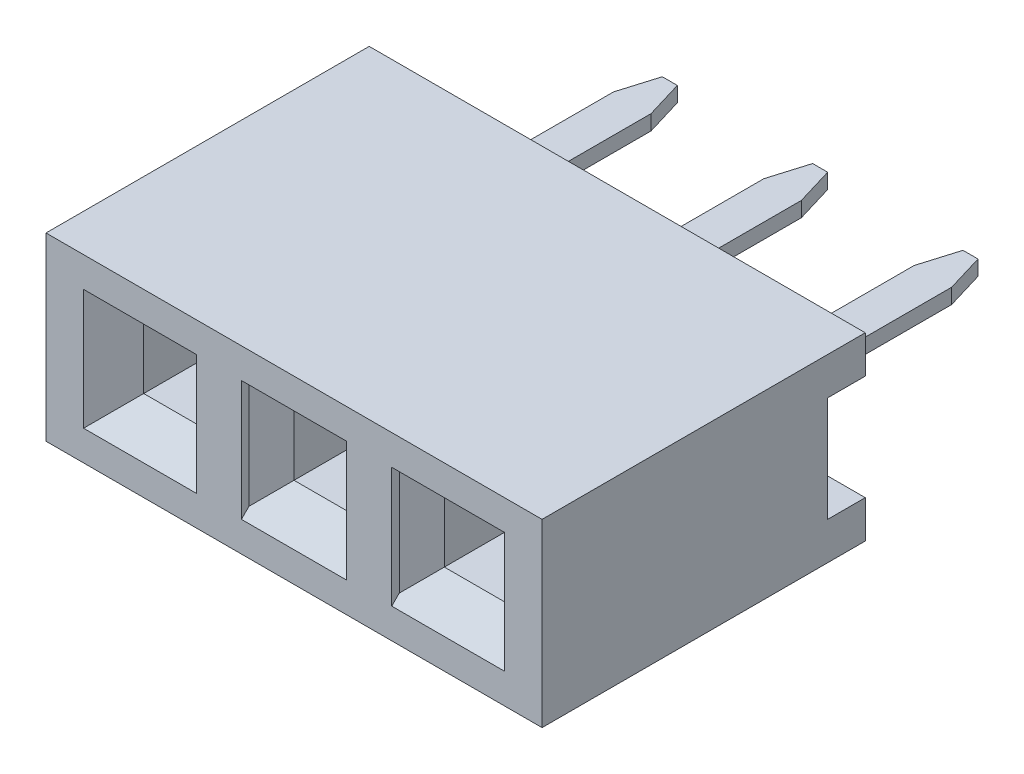
SolidWorks part; units mm, degrees
ref_plane "Front Plane" through (0, 0, 0) normal (0, 0, 1) x (1, 0, 0)
ref_plane "Top Plane" through (0, 0, 0) normal (0, 1, 0) x (1, 0, 0)
ref_plane "Right Plane" through (0, 0, 0) normal (1, 0, 0) x (0, 0, -1)
sketch "Sketch1" plane through (0, 0, 0) normal (1, 0, 0) x (0, -1, 0)
  line L0 (0, 0) -> (0, -4.3) construction
  line L1 (-1.2, 0) -> (1.2, 0)
  line L2 (-1.2, 0) -> (-1.2, -4.3)
  line L3 (-1.2, -4.3) -> (1.2, -4.3)
  line L4 (1.2, 0) -> (1.2, -4.3)
  point P0 (0, 0)
  dimension "D1" = 2.4
  dimension "D2" = 4.3
extrude "Boss-Extrude1" add sketch "Sketch1" along normal mid plane 2.6
sketch "Эскиз1" plane through (1.3, 0, 0) normal (1, 0, 0) x (0, 0, -1)
  line L0 (0, -0.7) -> (-0.5, -0.7)
  line L1 (0, -1.2) -> (0, 1.2) construction
  line L2 (-0.5, -0.7) -> (-0.5, 0.7)
  line L4 (-0.5, 0.7) -> (0, 0.7)
  line L5 (0, 0.7) -> (0, -0.7)
  line L6 (-4.3, -1.2) -> (0, -1.2) construction
  dimension "D1" = 0.5
  dimension "D2" = 0.5
  dimension "D3" = 0.5
extrude "Вырез-Вытянуть1" cut sketch "Эскиз1" against normal through all
sketch "Sketch2" plane through (0, 0, 4.3) normal (0, 0, 1) x (-1, 0, 0)
  line L0 (0, -1.2) -> (0, 1.2) construction
  line L3 (-1.3, -1.2) -> (1.3, -1.2) construction
  line L4 (-0.4, 0.4) -> (0.4, 0.4)
  line L5 (-0.4, 0.4) -> (-0.4, -0.4)
  line L6 (-0.4, -0.4) -> (0.4, -0.4)
  line L7 (0.4, 0.4) -> (0.4, -0.4)
  line L8 (-0.4, 0.4) -> (0.4, -0.4) construction
  line L9 (-0.4, -0.4) -> (0.4, 0.4) construction
  line L10 (-1.3, 1.2) -> (1.3, 1.2) construction
  point P5 (0, 0)
  dimension "D1" = 0.8
extrude "Cut-Extrude1" cut sketch "Sketch2" against normal offset from surface (3.1 mm away) 0.7 up to face at (0, 0, 0.5)
chamfer "Фаска1" distance 0.4 angle 45 4 edges at (0, -0.4, 4.3) (0.4, 0, 4.3) (0, 0.4, 4.3) (-0.4, 0, 4.3)
sketch "Sketch3" plane through (0, 0, 0) normal (0, 1, 0) x (1, 0, 0)
  line L0 (-0.25, 0) -> (-0.25, 2.2)
  line L1 (0.25, 0) -> (0.25, -0.5)
  line L2 (-0.25, 2.2) -> (-0.1, 2.7)
  line L3 (-0.1, 2.7) -> (0.1, 2.7)
  line L4 (0, 2.7) -> (0, 0) construction
  line L5 (-0.25, 0) -> (0.25, 0) construction
  line L6 (0.25, 2.2) -> (0.1, 2.7)
  line L7 (0.25, 0) -> (0.25, 2.2)
  line L8 (0.25, -0.5) -> (-0.25, -0.5)
  line L9 (-0.25, -0.5) -> (-0.25, 0)
  line L10 (-1.3, -0.5) -> (1.3, -0.5) construction
  line L11 (0.25, 2.2) -> (-0.25, 2.2) construction
  line L12 (0.4, -1.2) -> (-0.4, -1.2)
  line L13 (-0.4, -1.2) -> (-0.4, -3.1)
  line L14 (-0.4, -3.1) -> (-0.3, -3.1)
  line L15 (-0.3, -3.1) -> (-0.3, -1.3)
  line L16 (-0.3, -1.3) -> (0.3, -1.3)
  line L17 (0.3, -1.3) -> (0.3, -3.1)
  line L18 (0.3, -3.1) -> (0.4, -3.1)
  line L19 (0.4, -3.1) -> (0.4, -1.2)
  line L20 (-0.4, -1.2) -> (-0.4, -3.9) construction
  line L21 (0.4, -1.2) -> (0.4, -3.9) construction
  line L22 (0.4, -1.2) -> (-0.4, -1.2) construction
  dimension "D1" = 0.5
  dimension "D2" = 0.15
  dimension "D3" = 2.7
  dimension "D4" = 0.5
  dimension "D5" = 1.2
  dimension "D6" = 0.1
  dimension "D7" = 0.1
extrude "Boss-Extrude2" add sketch "Sketch3" along normal mid plane 0.2
pattern_linear "LPattern1" count 3 spacing 2 along (1, 0, 0) of bodies 103
combine bodies "Соединить1" operation type add bodies to combine 104 103 107
